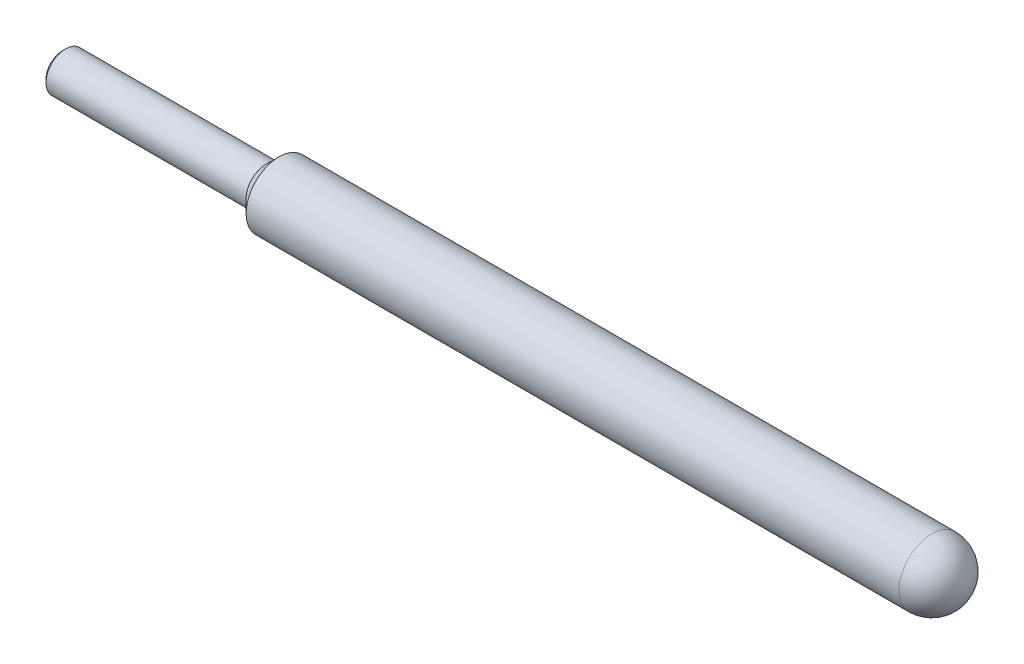
SolidWorks part; units mm, degrees
ref_plane "Front Plane" through (0, 0, 0) normal (0, 0, 1) x (1, 0, 0)
ref_plane "Top Plane" through (0, 0, 0) normal (0, 1, 0) x (1, 0, 0)
ref_plane "Right Plane" through (0, 0, 0) normal (1, 0, 0) x (0, 0, -1)
sketch "Sketch1" plane through (0, 0, 0) normal (0, 0, 1) x (1, 0, 0)
  line L0 (-137.5, 0) -> (137.5, 0)
  line L1 (-137.5, 0) -> (-137.5, 6)
  line L2 (-137.5, 6) -> (-75.5, 6)
  line L4 (-71.5, 10) -> (137.5, 10)
  line L5 (137.5, 10) -> (137.5, 0)
  line L6 (-75.5, 6) -> (-71.5, 10)
  point P3 (0, 0)
  dimension "D1" = 275
  dimension "D2" = 6
  dimension "D3" = 10
  dimension "D4" = 62
revolve "Revolve1" add sketch "Sketch1" angle 360 about L0
fillet "Fillet1" radius 10 1 edges at (137.5, 0, 10)
chamfer "Chamfer1" distance 1 angle 45 1 edges at (-137.5, 0, 6)
